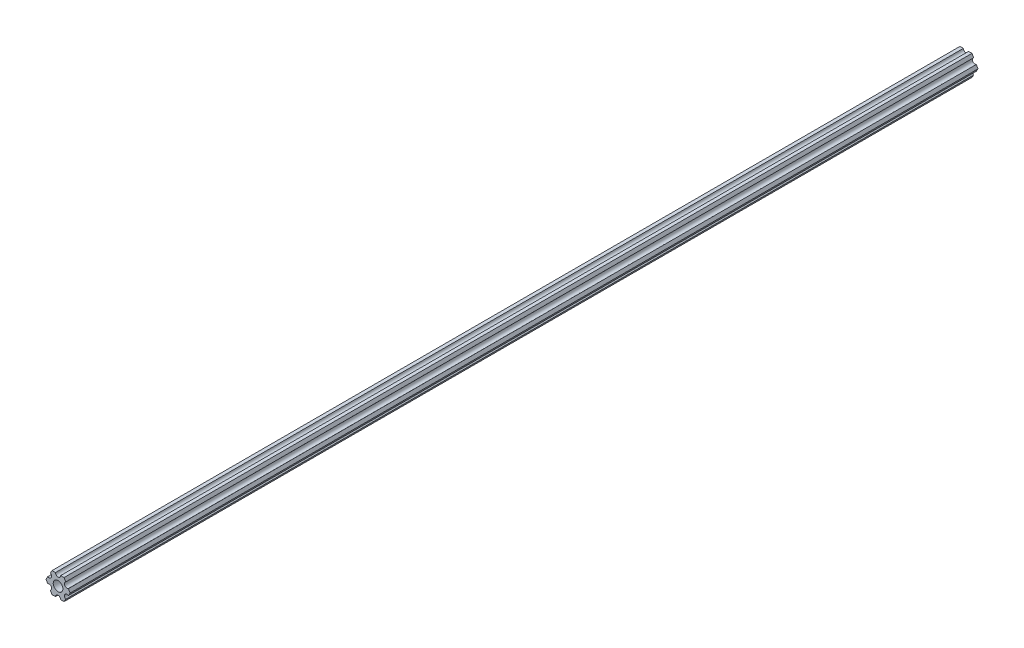
SolidWorks part; units mm, degrees
ref_plane "Front Plane" through (0, 0, 0) normal (0, 0, 1) x (1, 0, 0)
ref_plane "Top Plane" through (0, 0, 0) normal (0, 1, 0) x (1, 0, 0)
ref_plane "Right Plane" through (0, 0, 0) normal (1, 0, 0) x (0, 0, -1)
ref_plane "Plane1" through (0, 0, 0) normal (0, 0, -1) x (-1, 0, 0)
sketch "Sketch1" plane through (0, 0, 0) normal (0, 0, -1) x (-1, 0, 0)
  line L0 (-4.7055, -4.5498) -> (-3.6662, -6.35)
  line L1 (-3.6662, -6.35) -> (-1.5875, -6.35)
  line L2 (1.5875, -6.35) -> (3.6662, -6.35)
  line L3 (3.6662, -6.35) -> (4.7055, -4.5498)
  line L4 (6.293, -1.8002) -> (7.3323, 0)
  line L5 (7.3323, 0) -> (6.293, 1.8002)
  line L6 (4.7055, 4.5498) -> (3.6662, 6.35)
  line L7 (3.6662, 6.35) -> (1.5875, 6.35)
  line L8 (-1.5875, 6.35) -> (-3.6662, 6.35)
  line L9 (-3.6662, 6.35) -> (-4.7055, 4.5498)
  line L10 (-6.293, 1.8002) -> (-7.3323, 0)
  line L11 (-7.3323, 0) -> (-6.293, -1.8002)
  circle A0 centre (0, 0) radius 2.9337
  arc A1 (-6.293, -1.8002) -> (-4.7055, -4.5498) centre (-5.4993, -3.175) cw
  arc A2 (-1.5875, -6.35) -> (1.5875, -6.35) centre (0, -6.35) cw
  arc A3 (4.7055, -4.5498) -> (6.293, -1.8002) centre (5.4993, -3.175) cw
  arc A4 (6.293, 1.8002) -> (4.7055, 4.5498) centre (5.4993, 3.175) cw
  arc A5 (1.5875, 6.35) -> (-1.5875, 6.35) centre (0, 6.35) cw
  arc A6 (-4.7055, 4.5498) -> (-6.293, 1.8002) centre (-5.4993, 3.175) cw
extrude "Boss-Extrude1" add sketch "Sketch1" against normal blind 552.45
